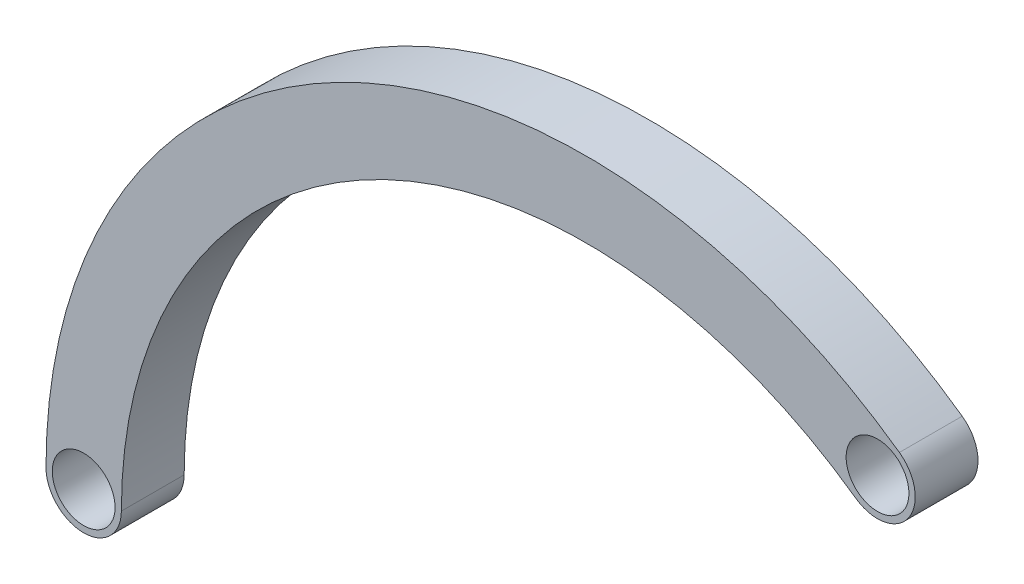
SolidWorks part; units mm, degrees
ref_plane "Front Plane" through (0, 0, 0) normal (0, 0, 1) x (1, 0, 0)
ref_plane "Top Plane" through (0, 0, 0) normal (0, 1, 0) x (1, 0, 0)
ref_plane "Right Plane" through (0, 0, 0) normal (1, 0, 0) x (0, 0, -1)
sketch "Sketch1" plane through (0, 0, 0) normal (0, 0, 1) x (1, 0, 0)
  line L0 (21.6751, 35.5556) -> (20.3007, 38.2222) construction
  line L1 (20.3007, 38.2222) -> (29.1896, 42.8035) construction
  arc A0 (0, 0) -> (63.2099, 32.5776) centre (40, 0) cw construction
  arc A1 (64.9506, 35.0209) -> (-3, 0) centre (40, 0) ccw
  arc A2 (61.4691, 30.1343) -> (3, 0) centre (40, 0) ccw
  arc A3 (61.4691, 30.1343) -> (64.9506, 35.0209) centre (63.2099, 32.5776) ccw
  arc A4 (-3, 0) -> (3, 0) centre (0, 0) ccw
  circle A5 centre (0, 0) radius 2.5
  circle A6 centre (63.2099, 32.5776) radius 2.5
  point P3 (21.6751, 35.5556)
  point P19 (20.3007, 38.2222)
  dimension "D1" = 40
  dimension "D2" = 3
  dimension "D4" = 5
  dimension "D5" = 5
  dimension "D7" = 90
extrude "Boss-Extrude1" add sketch "Sketch1" along normal blind 5 contours A2 A4 A1 A3 | A5 | A6
ref_plane "Plane1" through (-11.3042, 21.9334, 0) normal (-0.4581, 0.8889, 0) x (0.8889, 0.4581, 0)
sketch "Sketch2" plane through (-11.3042, 21.9334, 0) normal (-0.4581, 0.8889, 0) x (0.8889, 0.4581, 0)
  circle A0 centre (35.5556, -2.5) radius 2.5
  dimension "D1" = 2.5
  dimension "D3" = 5
  dimension "D2" = 0
